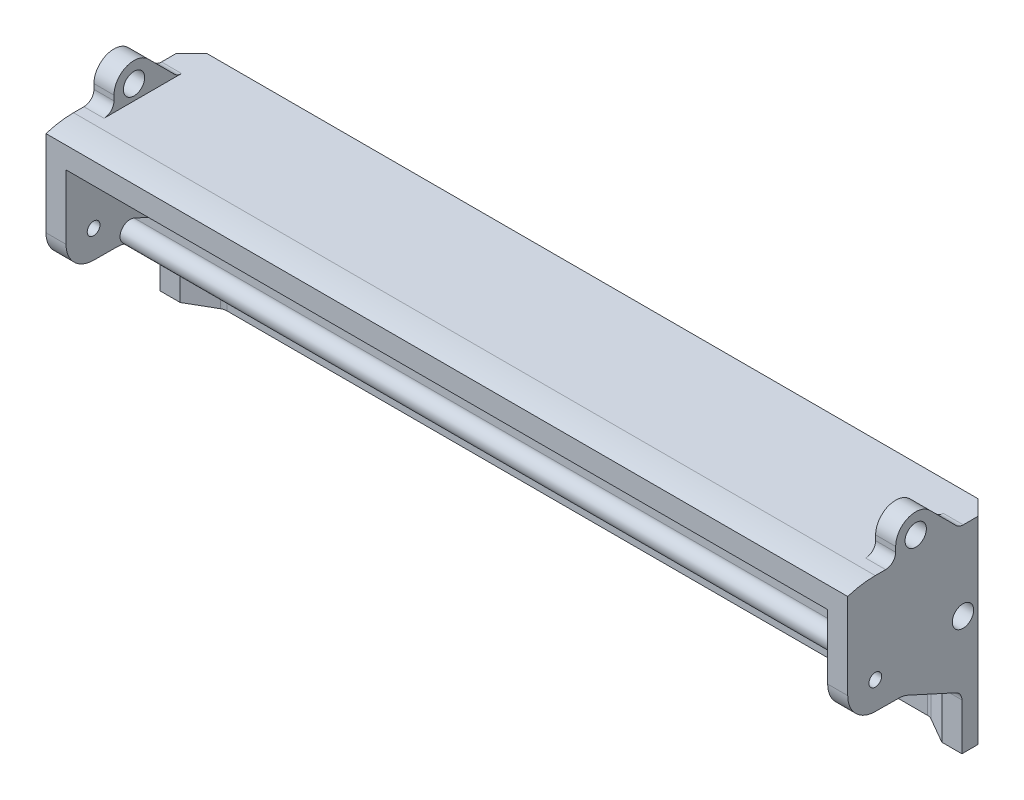
SolidWorks part; units mm, degrees
material "PET"
ref_plane "Front Plane" through (0, 0, 0) normal (0, 0, 1) x (1, 0, 0)
ref_plane "Top Plane" through (0, 0, 0) normal (0, 1, 0) x (1, 0, 0)
ref_plane "Right Plane" through (0, 0, 0) normal (1, 0, 0) x (0, 0, -1)
sketch "Sketch1" plane through (0, 0, 0) normal (1, 0, 0) x (0, 0, -1)
  line L3 (-34.036, 0) -> (42.164, 0) construction
  line L4 (-34.036, 0) -> (-34.036, 28.956) construction
  line L5 (-34.036, 28.956) -> (42.164, 28.956) construction
  line L11 (19.8576, 39.1492) -> (42.164, 28.956)
  line L12 (42.164, 28.956) -> (42.164, 0) construction
  line L13 (42.164, 28.956) -> (42.164, 14.4653)
  line L14 (46.99, 14.4653) -> (46.99, 77.089)
  line L15 (42.164, 14.4653) -> (46.99, 14.4653)
  line L16 (0.889, 48.514) -> (0.889, 75.7224)
  line L17 (9.5529, 39.783) -> (17.2674, 39.7235)
  line L18 (9.6202, 77.089) -> (46.99, 77.089)
  line L20 (37.4015, 52.0954) -> (69.4015, 52.0954) construction
  circle A0 centre (9.6202, 48.514) radius 2.0193
  arc A2 (0.889, 48.514) -> (9.5529, 39.783) centre (9.6202, 48.514) ccw
  circle A7 centre (21.1772, 42.037) radius 3.175 construction
  arc A8 (19.8576, 39.1492) -> (17.2674, 39.7235) centre (17.2184, 33.3737) ccw
  arc A9 (9.6202, 77.089) -> (0.889, 75.7224) centre (9.6202, 48.514) ccw
  circle A14 centre (37.4015, 52.0954) radius 3.3782
  point P9 (0.889, 48.514)
  point P22 (35.306, 84.2009)
  point P23 (35.306, 68.4833)
  dimension "D2" = 4.0386
  dimension "D5" = 0.889
  dimension "D6" = 17.4625
  dimension "D8" = 6.35
  dimension "D13" = 6.35
  dimension "D14" = 28.575
  dimension "D15" = 9.5885
  dimension "D20" = 6.7564
  dimension "D3" = 42.037
  dimension "D4" = 48.514
  dimension "D7" = 11.557
  dimension "D9" = 28.956
  dimension "D10" = 76.2
  dimension "D11" = 41.275
  dimension "D12" = 14.4653
  dimension "D16" = 4.826
  dimension "D18" = 52.0954
  dimension "D21" = 32
  dimension "D22" = 36.5125
extrude "Boss-Extrude1" add sketch "Sketch1" against normal blind 6.35
sketch "Sketch2" plane through (0, 0, 0) normal (1, 0, 0) x (0, 0, -1)
  line L0 (22.4969, 44.9248) -> (42.164, 35.9376)
  line L1 (42.164, 35.9376) -> (42.164, 70.739)
  line L2 (42.164, 70.739) -> (40.64, 70.739)
  line L3 (40.64, 70.739) -> (9.6202, 70.739)
  line L4 (46.99, 14.4653) -> (46.99, 77.089)
  line L5 (46.99, 77.089) -> (9.6202, 77.089)
  line L6 (46.99, 14.4653) -> (46.99, 77.089)
  line L7 (46.99, 77.089) -> (9.6202, 77.089)
  line L8 (0.889, 48.514) -> (0.889, 75.7224) construction
  line L9 (0.889, 68.9521) -> (0.889, 75.7224)
  line L10 (46.99, 14.4653) -> (42.164, 14.4653)
  line L11 (42.164, 14.4653) -> (42.164, 28.956)
  line L12 (19.8576, 39.1492) -> (42.164, 28.956)
  line L13 (40.64, 14.4653) -> (40.64, 70.739) construction
  circle A0 centre (21.1772, 42.037) radius 3.175
  arc A1 (9.6202, 70.739) -> (2.8293, 69.6761) centre (9.6202, 48.514) ccw
  arc A2 (9.6202, 77.089) -> (0.889, 75.7224) centre (9.6202, 48.514) ccw
  arc A3 (9.6202, 77.089) -> (0.889, 75.7224) centre (9.6202, 48.514) ccw
  arc A4 (2.8293, 69.6761) -> (0.889, 68.9521) centre (9.6202, 48.514) ccw
  circle A5 centre (21.1772, 42.037) radius 3.175 construction
  dimension "D1" = 0
  dimension "D2" = 6.35
extrude "Boss-Extrude2" add sketch "Sketch2" along normal blind 120.65
sketch "Sketch5" plane through (0, 14.4653, 0) normal (0, -1, 0) x (1, 0, 0)
  line L0 (17.2, -46.99) -> (0, -37.0596)
  line L1 (-6.35, -46.99) -> (120.65, -46.99) construction
  line L2 (-6.35, -37.0596) -> (-6.35, -46.99)
  line L3 (-6.35, -46.99) -> (17.2, -46.99)
  line L4 (4.5, -46.99) -> (-6.35, -40.7257)
  line L5 (-6.35, -37.0596) -> (0, -37.0596)
  line M6 (120.65, -42.164) -> (-6.35, -42.164)
  dimension "D1" = 30
  dimension "D2" = 23.55
  dimension "D3" = 6.35
  dimension "D4" = 9.9304
extrude "Boss-Extrude3" add sketch "Sketch5" against normal up to surface (14.4907 mm away) contours L5 L2 L4 L0 M6 | L4 L2 M6
sketch "Sketch6" plane through (-6.35, 0, 0) normal (-1, 0, 0) x (0, 0, 1)
  line L0 (-26.9183, 86.3416) -> (-36.171, 77.089)
  line L1 (-9.6202, 77.089) -> (-46.99, 77.089) construction
  line L2 (-16.0782, 81.8515) -> (-16.0782, 77.089)
  line L3 (-36.171, 77.089) -> (-16.0782, 77.089)
  circle A0 centre (-22.4282, 81.8515) radius 3.3782
  circle A1 centre (-37.4015, 52.0954) radius 3.3782 construction
  arc A2 (-16.0782, 81.8515) -> (-26.9183, 86.3416) centre (-22.4282, 81.8515) ccw
  point P3 (-37.4015, 52.0954)
  dimension "D1" = 14.9733
  dimension "D3" = 29.7561
  dimension "D4" = 6.35
  dimension "D2" = 4.7625
  dimension "D5" = 45
extrude "Boss-Extrude4" add sketch "Sketch6" against normal up to surface (6.35 mm away) up to face at (0, 52.0954, -40.7797)
fillet "Fillet2" radius 3.175 8 edges at (64.7456, 28.956, -42.164) (60.325, 35.9376, -42.164) (60.325, 70.739, -42.164) (4.4206, 30.1223, -39.6118) (8.8411, 21.7106, -42.164) (-3.175, 31.2885, -37.0596) (-3.175, 77.089, -36.171) (-3.175, 77.089, -16.0782)
mirror "Mirror1" about plane through (120.65, 0, 0) normal (1, 0, 0) of bodies 107 103
sketch "Sketch4" plane through (0, 0, -46.99) normal (0, 0, -1) x (-1, 0, 0)
  line L0 (-120.65, -112.5347) -> (-278.9619, 45.7771) construction
  line L1 (-120.65, -112.5347) -> (37.6619, 45.7772) construction
  line L2 (-278.9619, 45.7771) -> (-120.65, 204.089) construction
  line L3 (37.6619, 45.7772) -> (-120.65, 204.089) construction
  line L4 (-120.65, -112.5347) -> (-120.65, 204.089) construction
  line L5 (-278.9619, 45.7771) -> (37.6619, 45.7772) construction
  point P1 (-120.65, 45.7771)
  dimension "D1" = 223.8868
chamfer "Chamfer1" distance 4.826 angle 45 2 edges at (247.65, 45.7771, -46.99) (-6.35, 45.7771, -46.99)
